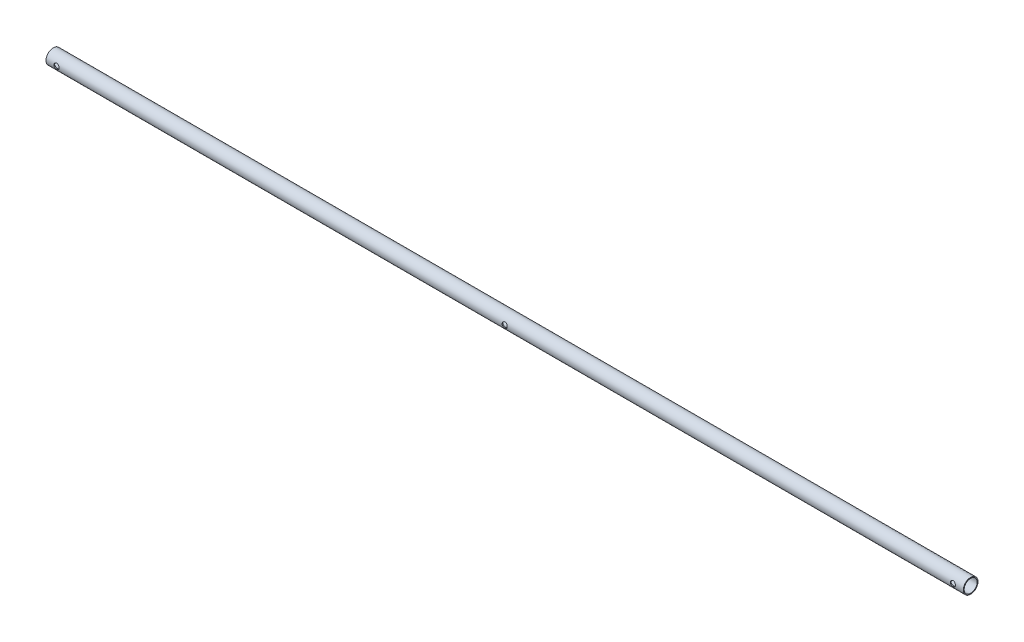
SolidWorks part; units mm, degrees
material "Galvanized Steel"
ref_plane "Front Plane" through (0, 0, 0) normal (0, 0, 1) x (1, 0, 0)
ref_plane "Top Plane" through (0, 0, 0) normal (0, 1, 0) x (1, 0, 0)
ref_plane "Right Plane" through (0, 0, 0) normal (1, 0, 0) x (0, 0, -1)
sketch "Sketch1" plane through (0, 0, 0) normal (1, 0, 0) x (0, 0, -1)
  circle A0 centre (0, 0) radius 7.8994
  circle A1 centre (0, 0) radius 8.9662
  dimension "D1" = 15.7988
  dimension "D2" = 17.9324
extrude "Boss-Extrude1" add sketch "Sketch1" along normal blind 1117.6
sketch "Sketch2" plane through (0, 0, 0) normal (0, 0, 1) x (1, 0, 0)
  line L0 (0, 8.9662) -> (0, -8.9662) construction
  line L1 (1117.6, -8.9662) -> (1117.6, 8.9662) construction
  circle A0 centre (558.8, 0) radius 3.175
  circle A1 centre (12.7, 0) radius 3.175
  circle A2 centre (1104.9, 0) radius 3.175
  dimension "D1" = 558.8
  dimension "D2" = 12.7
  dimension "D3" = 12.7
extrude "Cut-Extrude1" cut sketch "Sketch2" against normal through all and the other way through all
equation "\"extrudelength\"=44"
equation "\"D1@Boss-Extrude1\"=\"extrudelength\""
equation "\"D1@Sketch2\"=\"extrudelength\"/2"
